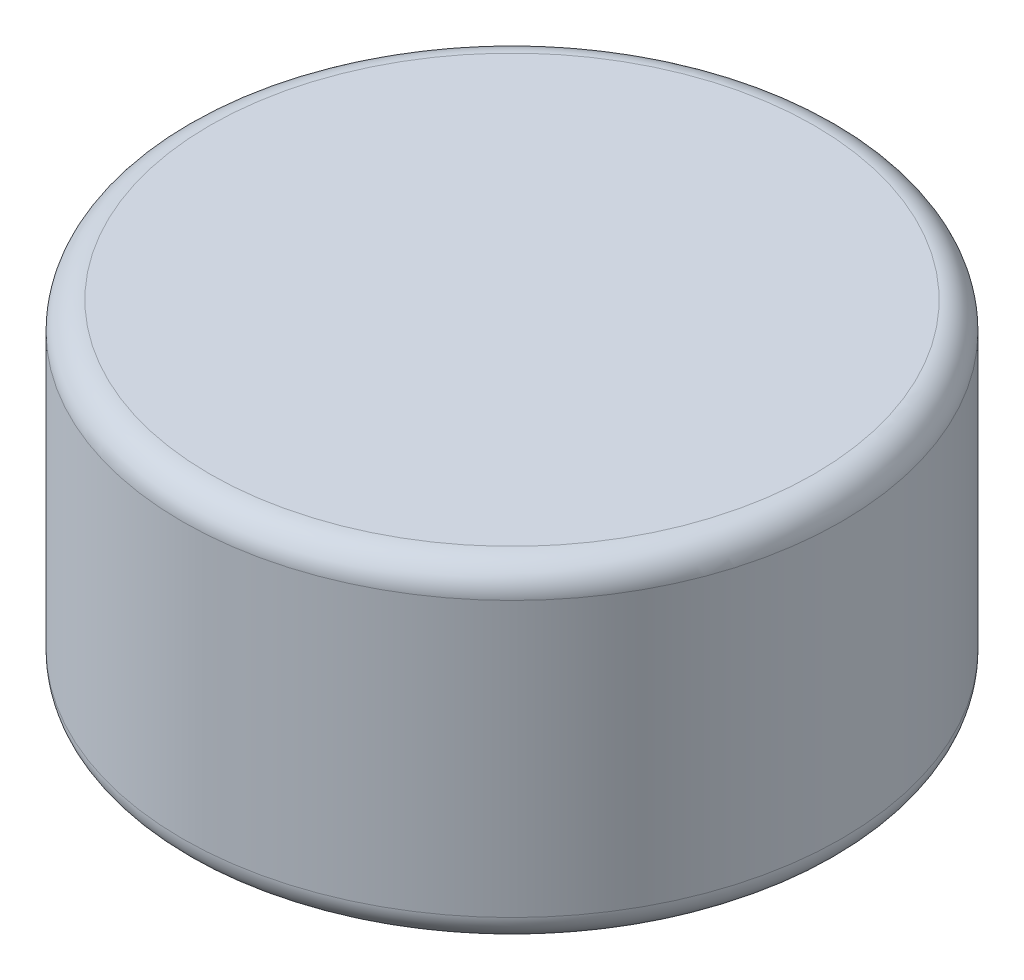
SolidWorks part; units mm, degrees
ref_plane "Front Plane" through (0, 0, 0) normal (0, 0, 1) x (1, 0, 0)
ref_plane "Top Plane" through (0, 0, 0) normal (0, 1, 0) x (1, 0, 0)
ref_plane "Right Plane" through (0, 0, 0) normal (1, 0, 0) x (0, 0, -1)
sketch "Sketch1" plane through (0, 0, 0) normal (0, 1, 0) x (1, 0, 0)
  circle A0 centre (0, 0) radius 3
extrude "Boss-Extrude1" add sketch "Sketch1" along normal blind 3
fillet "Fillet1" radius 0.25 2 edges at (0, 0, 3) (0, 3, 3)
